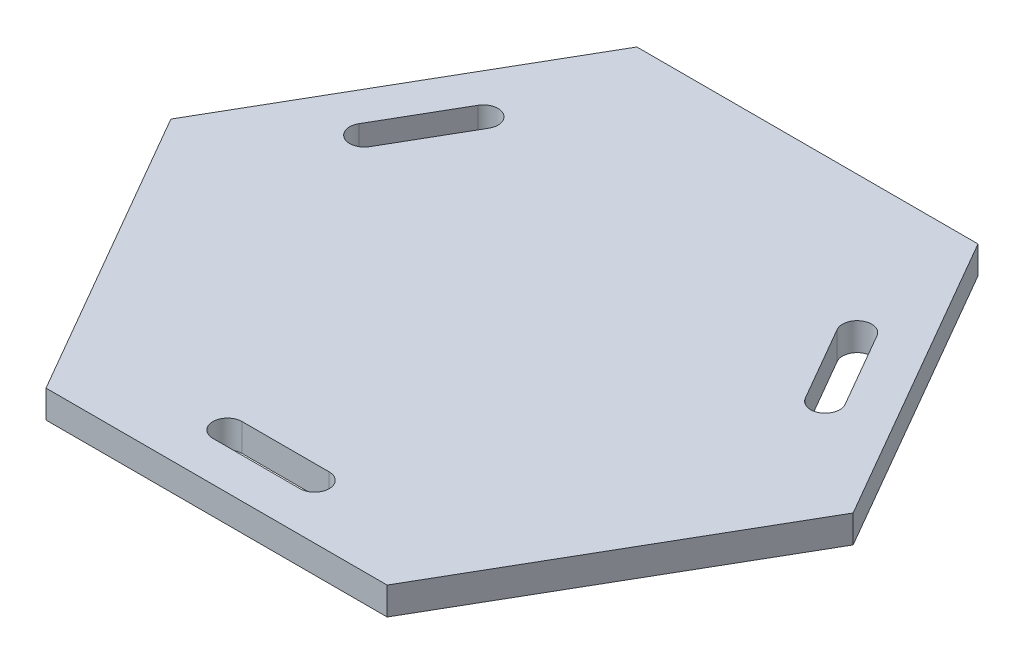
SolidWorks part; units mm, degrees
material "Oak"
ref_plane "Front Plane" through (0, 0, 0) normal (0, 0, 1) x (1, 0, 0)
ref_plane "Top Plane" through (0, 0, 0) normal (0, 1, 0) x (1, 0, 0)
ref_plane "Right Plane" through (0, 0, 0) normal (1, 0, 0) x (0, 0, -1)
sketch "Sketch1" plane through (0, 0, 0) normal (0, 1, 0) x (1, 0, 0)
  line L1 (-234.6351, 0) -> (-117.3176, -203.2)
  line L2 (-117.3176, -203.2) -> (117.3176, -203.2)
  line L3 (117.3176, -203.2) -> (234.6351, 0)
  line L4 (234.6351, 0) -> (117.3176, 203.2)
  line L5 (117.3176, 203.2) -> (-117.3176, 203.2)
  line L6 (-117.3176, 203.2) -> (-234.6351, 0)
  circle A0 centre (0, 0) radius 203.2 construction
  dimension "D1" = 406.4
extrude "Boss-Extrude1" add sketch "Sketch1" along normal blind 19.05
sketch "Sketch2" plane through (0, 19.05, 0) normal (0, 1, 0) x (1, 0, 0)
  line L0 (-29.972, -165.735) -> (29.972, -165.735) construction
  line L1 (-29.972, -155.702) -> (29.972, -155.702)
  line L2 (-29.972, -175.768) -> (29.972, -175.768)
  line L3 (-117.3176, -203.2) -> (117.3176, -203.2) construction
  line L4 (-128.5447, 108.824) -> (-158.5167, 56.911) construction
  line L5 (-119.8559, 103.8075) -> (-149.8279, 51.8945)
  line L6 (-137.2336, 113.8405) -> (-167.2056, 61.9275)
  line L7 (158.5167, 56.911) -> (128.5447, 108.824) construction
  line L8 (149.8279, 51.8945) -> (119.8559, 103.8075)
  line L9 (167.2056, 61.9275) -> (137.2336, 113.8405)
  arc A0 (-29.972, -155.702) -> (-29.972, -175.768) centre (-29.972, -165.735) ccw
  arc A1 (29.972, -175.768) -> (29.972, -155.702) centre (29.972, -165.735) ccw
  arc A2 (-119.8559, 103.8075) -> (-137.2336, 113.8405) centre (-128.5447, 108.824) ccw
  arc A3 (-167.2056, 61.9275) -> (-149.8279, 51.8945) centre (-158.5167, 56.911) ccw
  arc A4 (149.8279, 51.8945) -> (167.2056, 61.9275) centre (158.5167, 56.911) ccw
  arc A5 (137.2336, 113.8405) -> (119.8559, 103.8075) centre (128.5447, 108.824) ccw
  point P2 (0, -165.735)
  point P7 (-40.005, -165.735)
  point P8 (40.005, -165.735)
  point P16 (-143.5307, 82.8675)
  point P23 (143.5307, 82.8675)
  point P28 (0, 0)
  dimension "D1" = 80.01
  dimension "D2" = 27.432
  dimension "D3" = 20.066
  dimension "D4" = 3
extrude "Cut-Extrude1" cut sketch "Sketch2" against normal through all
